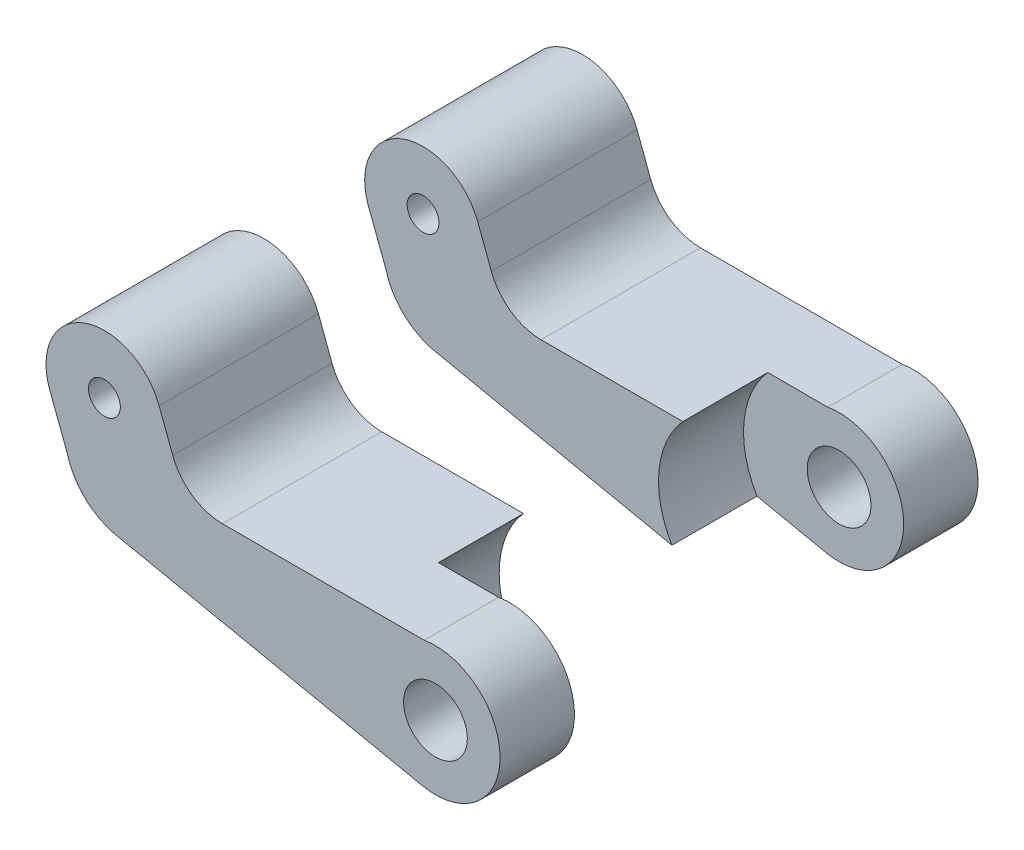
SolidWorks part; units mm, degrees
material "PET"
ref_plane "Front Plane" through (0, 0, 0) normal (0, 0, 1) x (1, 0, 0)
ref_plane "Top Plane" through (0, 0, 0) normal (0, 1, 0) x (1, 0, 0)
ref_plane "Right Plane" through (0, 0, 0) normal (1, 0, 0) x (0, 0, -1)
sketch "Sketch3" plane through (0, 0, 0) normal (0, 0, 1) x (1, 0, 0)
  line L0 (-15.1108, 40.908) -> (-13.8343, 37.5104)
  line L1 (-9.1537, 34.2689) -> (-1.6148, 34.2689) construction
  line L2 (-1.6148, 34.2689) -> (-9.1537, 34.2689) construction
  line L4 (-9.1537, 34.2689) -> (9.8465, 34.2689)
  line L5 (-18.7937, 28.2601) -> (9.6629, 22.3244)
  line L6 (-25.408, 37.0393) -> (-23.7698, 32.7498)
  arc A0 (-15.1108, 40.908) -> (-25.408, 37.0393) centre (-20.2594, 38.9736) ccw
  arc A1 (-13.8343, 37.5104) -> (-9.1537, 34.2689) centre (-9.1537, 39.2689) ccw
  arc A2 (9.6629, 22.3244) -> (9.8465, 34.2689) centre (10.9049, 28.2789) ccw
  arc A5 (-18.7937, 28.2601) -> (-23.7698, 32.7498) centre (-17.8653, 34.2915) cw
extrude "Boss-Extrude2" add sketch "Sketch3" along normal blind 15
sketch "Sketch7" plane through (0, 0, 15) normal (0, 0, 1) x (1, 0, 0)
  circle A0 centre (-20.2594, 38.9736) radius 1.5
  dimension "D1" = 3
extrude "Cut-Extrude1" cut sketch "Sketch7" against normal blind 18
sketch "Sketch11" plane through (0, 0, 0) normal (0, 0, -1) x (-1, 0, 0)
  circle A0 centre (-10.9049, 28.2789) radius 9
  dimension "D2" = 18
move or copy body "Body-Move/Copy1" bodies to move or copy 103 copy yes number of copies 1 translate (0, 0, 30)
sketch "Sketch12" plane through (0, 0, 15) normal (0, 0, 1) x (1, 0, 0)
  circle A0 centre (10.9049, 28.2789) radius 9
  dimension "D1" = 18
extrude "Cut-Extrude3" cut sketch "Sketch12" against normal blind 8 and the other way blind 69 contours A0
sketch "Sketch13" plane through (0, 0, 30) normal (0, 0, -1) x (-1, 0, 0)
  circle A0 centre (-10.9049, 28.2789) radius 9
extrude "Cut-Extrude4" cut sketch "Sketch13" against normal blind 8
sketch "Sketch14" plane through (0, 0, 0) normal (0, 0, -1) x (-1, 0, 0)
  circle A0 centre (-10.9049, 28.2789) radius 3
extrude "Cut-Extrude5" cut sketch "Sketch14" against normal blind 48 and the other way blind 10
